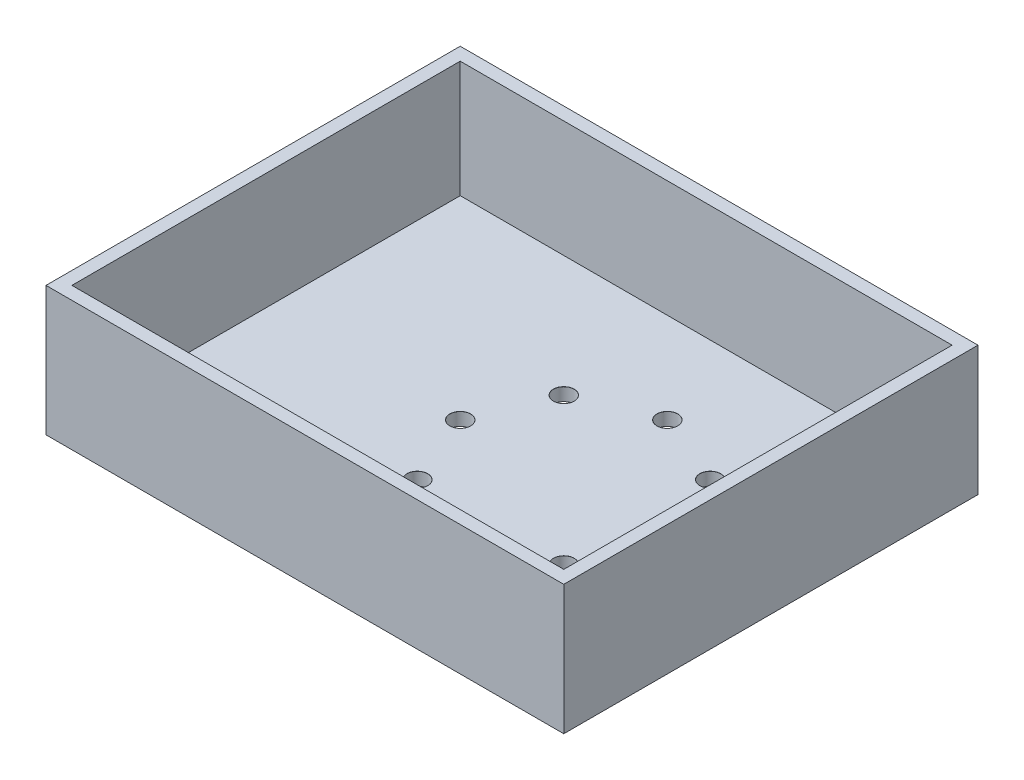
SolidWorks part; units mm, degrees
ref_plane "Front Plane" through (0, 0, 0) normal (0, 0, 1) x (1, 0, 0)
ref_plane "Top Plane" through (0, 0, 0) normal (0, 1, 0) x (1, 0, 0)
ref_plane "Right Plane" through (0, 0, 0) normal (1, 0, 0) x (0, 0, -1)
sketch "草图2" plane through (0, 0, 0) normal (0, 0, 1) x (1, 0, 0)
  line L11 (0, 0) -> (-200, 0)
  line L12 (0, 0) -> (0, 50)
  line L13 (0, 50) -> (-200, 50)
  line L14 (-200, 0) -> (-200, 50)
  dimension "D1" = 50
  dimension "D2" = 200
extrude "凸台-拉伸1" add sketch "草图2" along normal blind 160
shell "抽壳1" thickness 5
sketch "草图4" plane through (0, 5, 0) normal (0, 1, 0) x (1, 0, 0)
  line L0 (9.1016, -80) -> (-239.1186, -80) construction
  line L1 (-5, -155) -> (-5, -5) construction
  line L2 (0, -160) -> (0, 0) construction
  circle A0 centre (-80, -80) radius 40
  point P8 (0, -80)
  dimension "D2" = 80
  dimension "D1" = 75
hole_wizard "M8x1.0 螺纹孔1" positions "草图5" profile "草图6" tap size "M8x1.0" standard "GB" end condition through all
sketch "草图5" plane through (0, 5, 0) normal (0, 1, 0) x (1, 0, 0)
  circle A0 centre (-80, -80) radius 40 construction
  point P0 (-80, -40)
sketch "草图6" plane through (-80, 5, 40) normal (1, 0, 0) x (0, 0, 1)
  line L0 (0, 0) -> (0, 5)
  line L1 (0, 5) -> (4, 5)
  line L2 (4, 5) -> (4, 0.021)
  line L3 (4, 0.021) -> (4.025, 0)
  line L5 (4.025, 0) -> (0, 0)
  line L6 (-4, 0.021) -> (-4.025, 0) construction
  line L11 (0, -6.35) -> (0, 107.95) construction
  dimension "通孔螺纹孔钻头直径" = 8
  dimension "通孔螺纹孔钻头深度" = 5
  dimension "近端锥形沉头孔直径" = 8.05
  dimension "近端锥形沉头孔角度" = 100
cosmetic thread "孔螺蚊线1"
ref_plane "基准面1" through (0, 0, 80) normal (0, 0, 1) x (1, 0, 0)
sketch "草图8" plane through (0, 0, 80) normal (0, 0, 1) x (1, 0, 0)
  line L0 (-80, 5) -> (-80, 42.0412)
  line L1 (-40, 5) -> (-120, 5) construction
pattern_circular "阵列(圆周)1" count 8 over 360 about axis through (-80, 0, 80) along (0, 1, 0) of "M8x1.0 螺纹孔1"
cosmetic thread "孔螺蚊线2"
cosmetic thread "孔螺蚊线3"
cosmetic thread "孔螺蚊线4"
cosmetic thread "孔螺蚊线5"
cosmetic thread "孔螺蚊线6"
cosmetic thread "孔螺蚊线7"
cosmetic thread "孔螺蚊线8"
